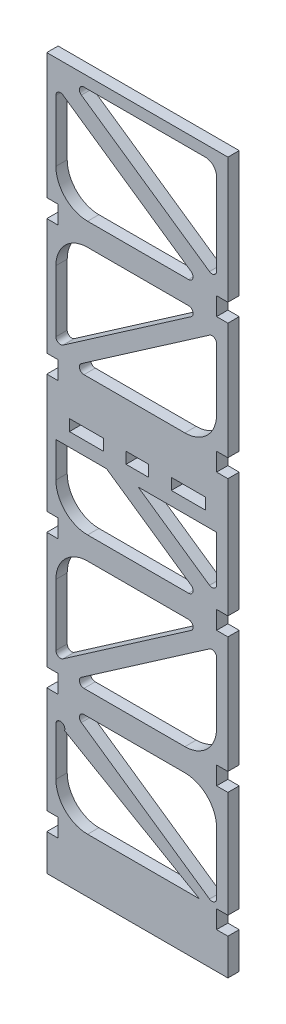
SolidWorks part; units mm, degrees
material "Balsa"
ref_plane "Front Plane" through (0, 0, 0) normal (0, 0, 1) x (1, 0, 0)
ref_plane "Top Plane" through (0, 0, 0) normal (0, 1, 0) x (1, 0, 0)
ref_plane "Right Plane" through (0, 0, 0) normal (1, 0, 0) x (0, 0, -1)
sketch "Model" plane through (0, 0, 0) normal (0, 0, 1) x (1, 0, 0)
  line L0 (77.47, 87.63) -> (20.8312, 87.63)
  line L1 (95.25, 35.3278) -> (95.25, 69.85)
  line L2 (19.3854, 83.0016) -> (91.2642, 33.2394)
  line L3 (5.1107, 145.4001) -> (5.1107, 110.8779)
  line L4 (79.5294, 163.1801) -> (22.8907, 163.1801)
  line L5 (9.0964, 108.7895) -> (80.9752, 158.5518)
  line L6 (77.47, 240.03) -> (20.8312, 240.03)
  line L7 (95.25, 187.7278) -> (95.25, 222.25)
  line L8 (19.3854, 235.4016) -> (91.2642, 185.6394)
  line L9 (22.8907, 175.8801) -> (79.5294, 175.8801)
  line L10 (5.1107, 228.1824) -> (5.1107, 193.6601)
  line L11 (80.9752, 180.5085) -> (9.0964, 230.2708)
  line L12 (91.2642, 154.7206) -> (19.3854, 104.9584)
  line L13 (95.25, 118.11) -> (95.25, 152.6322)
  line L14 (20.8312, 100.33) -> (77.47, 100.33)
  line L15 (5.1107, 297.8001) -> (5.1107, 263.2779)
  line L16 (79.5294, 315.5801) -> (22.8907, 315.5801)
  line L17 (9.0964, 261.1895) -> (80.9752, 310.9518)
  line L18 (88.9, 392.43) -> (20.8312, 392.43)
  line L19 (95.25, 340.1278) -> (95.25, 386.08)
  line L20 (19.3854, 387.8016) -> (91.2642, 338.0394)
  line L21 (22.8907, 328.2801) -> (79.5294, 328.2801)
  line L22 (5.1107, 380.5824) -> (5.1107, 346.0601)
  line L23 (80.9752, 332.9085) -> (9.0964, 382.6708)
  line L24 (22.8907, 30.48) -> (85.6262, 30.48)
  line L25 (5.1107, 75.6336) -> (5.1107, 48.26)
  line L26 (85.6262, 30.48) -> (10.006, 74.3482)
  line L27 (91.2642, 307.1206) -> (19.3854, 257.3584)
  line L28 (95.25, 270.51) -> (95.25, 305.0322)
  line L29 (20.8312, 252.73) -> (77.47, 252.73)
  line L30 (0, 398.78) -> (0, 0)
  line L31 (0, 0) -> (101.6, 0)
  line L32 (101.6, 398.78) -> (101.6, 0)
  line L33 (0, 398.78) -> (101.6, 398.78)
  arc A1 (91.2642, 33.2394) -> (95.25, 35.3278) centre (92.71, 35.3278) ccw
  arc A2 (20.8312, 87.63) -> (19.3854, 83.0016) centre (20.8312, 85.09) ccw
  arc A4 (80.9752, 158.5518) -> (79.5294, 163.1801) centre (79.5294, 160.6401) ccw
  arc A5 (5.1107, 110.8779) -> (9.0964, 108.7895) centre (7.6507, 110.8779) ccw
  arc A7 (91.2642, 185.6394) -> (95.25, 187.7278) centre (92.71, 187.7278) ccw
  arc A8 (20.8312, 240.03) -> (19.3854, 235.4016) centre (20.8312, 237.49) ccw
  arc A10 (9.0964, 230.2708) -> (5.1107, 228.1824) centre (7.6507, 228.1824) ccw
  arc A11 (79.5294, 175.8801) -> (80.9752, 180.5085) centre (79.5294, 178.4201) ccw
  arc A12 (95.25, 152.6322) -> (91.2642, 154.7206) centre (92.71, 152.6322) ccw
  arc A14 (19.3854, 104.9584) -> (20.8312, 100.33) centre (20.8312, 102.87) ccw
  arc A16 (80.9752, 310.9518) -> (79.5294, 315.5801) centre (79.5294, 313.0401) ccw
  arc A17 (5.1107, 263.2779) -> (9.0964, 261.1895) centre (7.6507, 263.2779) ccw
  arc A18 (95.25, 386.08) -> (88.9, 392.43) centre (88.9, 386.08) ccw
  arc A19 (91.2642, 338.0394) -> (95.25, 340.1278) centre (92.71, 340.1278) ccw
  arc A20 (20.8312, 392.43) -> (19.3854, 387.8016) centre (20.8312, 389.89) ccw
  arc A22 (9.0964, 382.6708) -> (5.1107, 380.5824) centre (7.6507, 380.5824) ccw
  arc A23 (79.5294, 328.2801) -> (80.9752, 332.9085) centre (79.5294, 330.8201) ccw
  arc A25 (10.006, 74.3482) -> (5.1107, 75.6336) centre (7.6137, 75.2018) ccw
  arc A27 (95.25, 305.0322) -> (91.2642, 307.1206) centre (92.71, 305.0322) ccw
  arc A29 (19.3854, 257.3584) -> (20.8312, 252.73) centre (20.8312, 255.27) ccw
  arc A30 (5.1107, 48.26) -> (22.8907, 30.48) centre (22.8907, 48.26) ccw
  arc A31 (5.1107, 346.0601) -> (22.8907, 328.2801) centre (22.8907, 346.0601) ccw
  arc A32 (5.1107, 297.8001) -> (22.8907, 315.5801) centre (22.8907, 297.8001) cw
  arc A33 (95.25, 270.51) -> (77.47, 252.73) centre (77.47, 270.51) cw
  arc A34 (77.47, 240.03) -> (95.25, 222.25) centre (77.47, 222.25) cw
  arc A35 (5.1107, 193.6601) -> (22.8907, 175.8801) centre (22.8907, 193.6601) ccw
  arc A36 (5.1107, 145.4001) -> (22.8907, 163.1801) centre (22.8907, 145.4001) cw
  arc A37 (77.47, 100.33) -> (95.25, 118.11) centre (77.47, 118.11) ccw
  arc A38 (77.47, 87.63) -> (95.25, 69.85) centre (77.47, 69.85) cw
  point P0 (84.088, 30.48)
  dimension "D3" = 6.35
  dimension "D4" = 2.54
  dimension "D5" = 2.54
  dimension "D6" = 2.54
  dimension "D7" = 2.54
  dimension "D8" = 2.54
  dimension "D9" = 2.54
  dimension "D10" = 2.54
  dimension "D11" = 2.54
  dimension "D12" = 2.54
  dimension "D13" = 2.54
  dimension "D14" = 2.54
  dimension "D15" = 2.54
  dimension "D16" = 2.54
  dimension "D17" = 2.54
  dimension "D18" = 2.54
  dimension "D19" = 2.54
  dimension "D20" = 2.54
  dimension "D21" = 2.54
  dimension "D26" = 17.78
  dimension "D27" = 17.78
  dimension "D1" = 398.78
  dimension "D2" = 101.6
  dimension "D25" = 87.4233
  dimension "D28" = 30.48
extrude "Boss-Extrude1" add sketch "Model" along normal blind 6.35
sketch "Sketch1" plane through (0, 0, 6.35) normal (0, 0, 1) x (1, 0, 0)
  line L0 (101.6, 0) -> (101.6, 398.78) construction
  line L1 (101.6, 328.2801) -> (95.25, 328.2801)
  line L2 (101.6, 328.2801) -> (101.6, 318.1201)
  line L3 (101.6, 318.1201) -> (95.25, 318.1201)
  line L4 (95.25, 328.2801) -> (95.25, 318.1201)
  line L5 (0, 398.78) -> (0, 0) construction
  line L6 (0, 252.73) -> (6.35, 252.73)
  line L7 (0, 252.73) -> (0, 242.57)
  line L8 (0, 242.57) -> (6.35, 242.57)
  line L9 (6.35, 252.73) -> (6.35, 242.57)
  line L10 (22.8907, 328.2801) -> (79.5294, 328.2801) construction
  line L11 (101.6, 175.8801) -> (95.25, 175.8801)
  line L12 (101.6, 175.8801) -> (101.6, 165.7201)
  line L13 (101.6, 165.7201) -> (95.25, 165.7201)
  line L14 (95.25, 175.8801) -> (95.25, 165.7201)
  line L15 (0, 100.33) -> (6.35, 100.33)
  line L16 (0, 100.33) -> (0, 90.17)
  line L17 (0, 90.17) -> (6.35, 90.17)
  line L18 (6.35, 100.33) -> (6.35, 90.17)
  line L19 (20.8312, 252.73) -> (77.47, 252.73) construction
  line L21 (20.8312, 100.33) -> (77.47, 100.33) construction
  line L22 (22.8907, 30.48) -> (85.6262, 30.48) construction
  line L23 (0, 328.2801) -> (6.35, 328.2801)
  line L24 (0, 328.2801) -> (0, 318.1201)
  line L25 (0, 318.1201) -> (6.35, 318.1201)
  line L26 (6.35, 328.2801) -> (6.35, 318.1201)
  line L27 (101.6, 252.73) -> (95.25, 252.73)
  line L28 (101.6, 252.73) -> (101.6, 242.57)
  line L29 (101.6, 242.57) -> (95.25, 242.57)
  line L30 (95.25, 252.73) -> (95.25, 242.57)
  line L31 (0, 175.8801) -> (6.35, 175.8801)
  line L32 (0, 175.8801) -> (0, 165.7201)
  line L33 (0, 165.7201) -> (6.35, 165.7201)
  line L34 (6.35, 175.8801) -> (6.35, 165.7201)
  line L35 (101.6, 100.33) -> (95.25, 100.33)
  line L36 (101.6, 100.33) -> (101.6, 90.17)
  line L37 (101.6, 90.17) -> (95.25, 90.17)
  line L38 (95.25, 100.33) -> (95.25, 90.17)
  line L39 (0, 30.48) -> (6.35, 30.48)
  line L40 (0, 30.48) -> (0, 20.32)
  line L41 (0, 20.32) -> (6.35, 20.32)
  line L42 (6.35, 30.48) -> (6.35, 20.32)
  line L43 (101.6, 30.48) -> (95.25, 30.48)
  line L44 (101.6, 30.48) -> (101.6, 20.32)
  line L45 (101.6, 20.32) -> (95.25, 20.32)
  line L46 (95.25, 30.48) -> (95.25, 20.32)
  line L47 (22.8907, 175.8801) -> (79.5294, 175.8801) construction
  dimension "D1" = 6.35
  dimension "D2" = 10.16
  dimension "D3" = 10.16
  dimension "D4" = 6.35
  dimension "D5" = 6.35
  dimension "D6" = 10.16
  dimension "D7" = 6.35
  dimension "D8" = 10.16
  dimension "D9" = 10.16
  dimension "D10" = 10.16
extrude "Cut-Extrude1" cut sketch "Sketch1" against normal up to surface (6.35 mm away) contours L1 L4 L3 L2 | L27 L30 L29 L28 | L9 L6 L7 L8 | L42 L39 L40 L41 | L11 L14 L13 L12 | L26 L25 L24 L23 | L43 L46 L45 L44 | L38 L37 L36 L35 | L15 L18 L17 L16 | L31 L34 L33 L32 up to face at (50.8, 199.39, 0)
sketch "Sketch2" plane through (0, 0, 6.35) normal (0, 0, 1) x (1, 0, 0)
  line L0 (77.47, 240.03) -> (20.8312, 240.03) construction
  line L1 (1.7778, 240.03) -> (97.5543, 240.03)
  line L2 (1.7778, 240.03) -> (1.7778, 213.36)
  line L3 (1.7778, 213.36) -> (97.5543, 213.36)
  line L4 (97.5543, 240.03) -> (97.5543, 213.36)
  dimension "D1" = 26.67
extrude "Boss-Extrude2" add sketch "Sketch2" against normal up to surface (6.35 mm away) up to face at (50.8, 174.9082, 0)
sketch "Sketch3" plane through (0, 0, 6.35) normal (0, 0, 1) x (1, 0, 0)
  line L1 (88.9, 227.33) -> (69.85, 227.33)
  line L2 (88.9, 227.33) -> (88.9, 220.98)
  line L3 (88.9, 220.98) -> (69.85, 220.98)
  line L4 (69.85, 227.33) -> (69.85, 220.98)
  line L5 (101.6, 175.8801) -> (101.6, 242.57) construction
  line L6 (0, 242.57) -> (0, 175.8801) construction
  line L7 (31.75, 220.98) -> (12.7, 220.98)
  line L8 (31.75, 220.98) -> (31.75, 227.33)
  line L9 (31.75, 227.33) -> (12.7, 227.33)
  line L10 (12.7, 220.98) -> (12.7, 227.33)
  line L12 (5.1107, 213.36) -> (33.5231, 213.36) construction
  line L13 (57.15, 220.98) -> (44.45, 220.98)
  line L14 (57.15, 220.98) -> (57.15, 227.33)
  line L15 (57.15, 227.33) -> (44.45, 227.33)
  line L16 (44.45, 220.98) -> (44.45, 227.33)
  line L17 (51.2233, 213.36) -> (95.25, 213.36) construction
  dimension "D2" = 6.35
  dimension "D3" = 12.7
  dimension "D4" = 19.05
  dimension "D5" = 12.7
  dimension "D6" = 19.05
  dimension "D7" = 6.35
  dimension "D8" = 7.62
  dimension "D9" = 12.7
  dimension "D10" = 12.7
  dimension "D11" = 7.62
extrude "Cut-Extrude2" cut sketch "Sketch3" against normal up to surface (6.35 mm away) up to face at (83.4048, 199.7204, 0)
equation "\"thick\"=0.25"
equation "\"D1@Boss-Extrude1\"=\"thick\""
